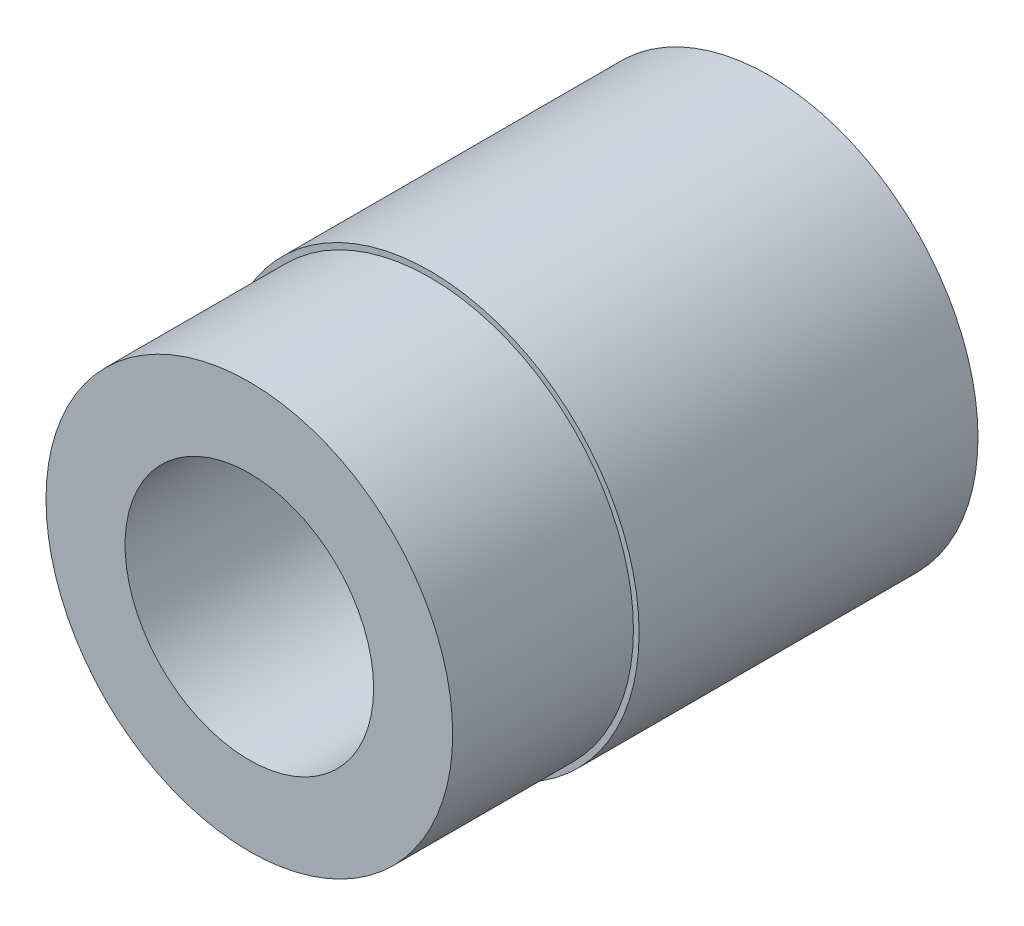
SolidWorks part; units mm, degrees
ref_plane "前视基准面" through (0, 0, 0) normal (0, 0, 1) x (1, 0, 0)
ref_plane "上视基准面" through (0, 0, 0) normal (0, 1, 0) x (1, 0, 0)
ref_plane "右视基准面" through (0, 0, 0) normal (1, 0, 0) x (0, 0, -1)
sketch "草图1" plane through (0, 0, 0) normal (0, 0, 1) x (1, 0, 0)
  circle A0 centre (0, 0) radius 18.5
  dimension "D1" = 37
extrude "拉伸1" add sketch "草图1" along normal blind 30
sketch "草图2" plane through (0, 0, 30) normal (0, 0, 1) x (1, 0, 0)
  circle A0 centre (0, 0) radius 18
extrude "拉伸2" add sketch "草图2" along normal blind 16
sketch "草图3" plane through (0, 0, 46) normal (0, 0, 1) x (1, 0, 0)
  circle A0 centre (0, 0) radius 11
extrude "切除-拉伸1" cut sketch "草图3" against normal blind 30
